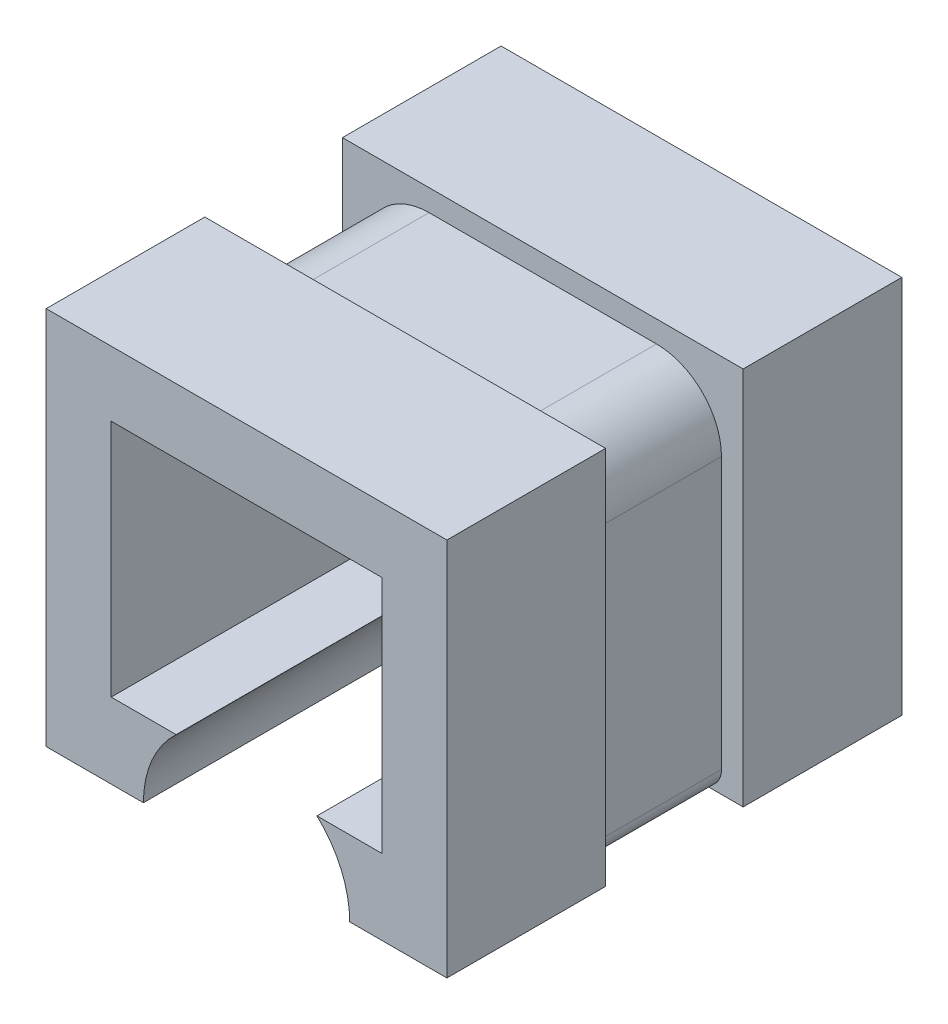
SolidWorks part; units mm, degrees
ref_plane "Front" through (0, 0, 0) normal (0, 0, 1) x (1, 0, 0)
ref_plane "Top" through (0, 0, 0) normal (0, 1, 0) x (1, 0, 0)
ref_plane "Right" through (0, 0, 0) normal (1, 0, 0) x (0, 0, -1)
sketch "Sketch1" plane through (0, 0, 0) normal (0, 0, 1) x (1, 0, 0)
  line L0 (-4.7625, 0) -> (-9.25, 0)
  line L1 (-9.25, 0) -> (-9.25, 17.5125)
  line L2 (-9.25, 17.5125) -> (9.25, 17.5125)
  line L3 (9.25, 17.5125) -> (9.25, 0)
  line L4 (9.25, 0) -> (4.7625, 0)
  line L5 (6.25, 3.4812) -> (6.25, 14.5125)
  line L6 (6.25, 14.5125) -> (-6.25, 14.5125)
  line L7 (-6.25, 14.5125) -> (-6.25, 3.4812)
  line L8 (-6.25, 3.4812) -> (-3.25, 3.4812)
  line L9 (6.25, 3.4812) -> (3.25, 3.4812)
  arc A0 (4.7625, 0) -> (3.25, 3.4812) centre (0, 0) ccw
  arc A1 (-3.25, 3.4812) -> (-4.7625, 0) centre (0, 0) ccw
  point P11 (9.25, 8.7563)
  dimension "D1" = 9.525
  dimension "D2" = 12.5
  dimension "D3" = 14.5125
  dimension "D4" = 3
  dimension "D5" = 3
  dimension "D6" = 3
extrude "Boss-Extrude1" add sketch "Sketch1" along normal mid plane 21
sketch "Sketch2" plane through (0, 0, 0) normal (0, 0, 1) x (1, 0, 0)
  line L0 (9.25, 17.5125) -> (-9.25, 17.5125) construction
  line L1 (-9.25, 17.5125) -> (-9.25, 0) construction
  line L2 (0, 17.5125) -> (-9.25, 17.5125)
  line L3 (-9.25, 17.5125) -> (-9.25, 0)
  line L4 (-9.25, 0) -> (-8.25, 0)
  line L5 (-8.25, 0) -> (-8.25, 16.5125)
  line L6 (-8.25, 16.5125) -> (0, 16.5125)
  line L7 (0, 16.5125) -> (0, 17.5125)
  dimension "D1" = 1
  dimension "D2" = 1
extrude "Cut-Extrude1" cut sketch "Sketch2" against normal mid plane 6.35
mirror "Mirror1" about plane through (0, 0, 0) normal (1, 0, 0) of "Cut-Extrude1"
fillet "Fillet1" radius 3 2 edges at (8.25, 16.5125, 0) (-8.25, 16.5125, 0)
fillet "Fillet2" radius 1 2 edges at (8.25, 0, 0) (-8.25, 0, 0)
